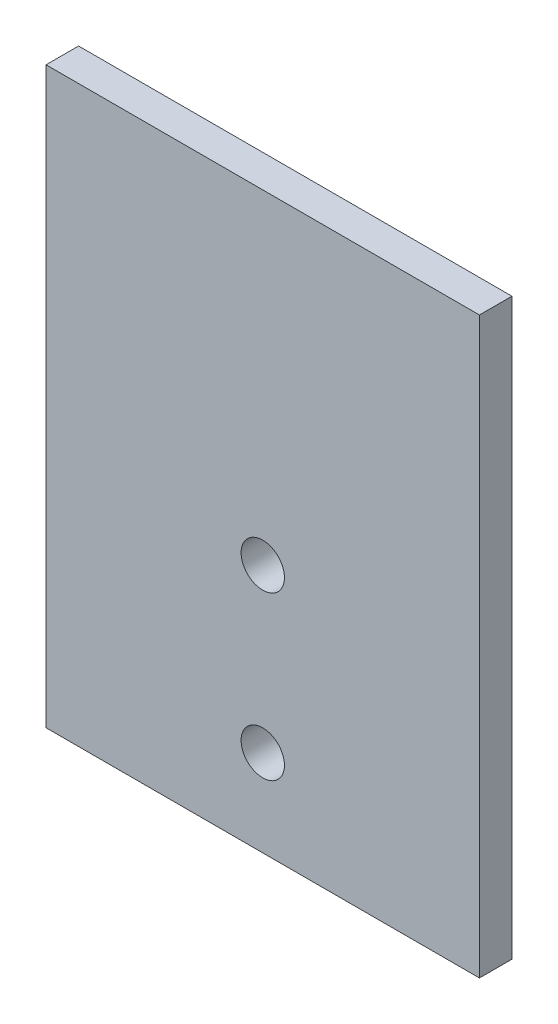
SolidWorks part; units mm, degrees
ref_plane "Piano frontale" through (0, 0, 0) normal (0, 0, 1) x (1, 0, 0)
ref_plane "Piano superiore" through (0, 0, 0) normal (0, 1, 0) x (1, 0, 0)
ref_plane "Piano destro" through (0, 0, 0) normal (1, 0, 0) x (0, 0, -1)
sketch "Schizzo1" plane through (0, 0, 0) normal (0, 0, 1) x (1, 0, 0)
  line L1 (-20, -26.5) -> (20, -26.5)
  line L2 (-20, -26.5) -> (-20, 26.5)
  line L3 (-20, 26.5) -> (20, 26.5)
  line L4 (20, -26.5) -> (20, 26.5)
  line L5 (-20, -26.5) -> (20, 26.5) construction
  line L6 (-20, 26.5) -> (20, -26.5) construction
  point P0 (0, 0)
  dimension "D1" = 40
  dimension "D2" = 53
extrude "Estrusione-Estrusione1" add sketch "Schizzo1" along normal blind 3
sketch "Schizzo2" plane through (0, 0, 3) normal (0, 0, 1) x (1, 0, 0)
  line L0 (-20, -26.5) -> (20, -26.5) construction
  line L1 (0, -55) -> (0, 55) construction
  circle A0 centre (0, -18.5) radius 2
  circle A1 centre (0, -3.5) radius 2
  dimension "D1" = 4
  dimension "D3" = 4
  dimension "D2" = 8
  dimension "D4" = 23
extrude "Taglio-Estrusione1" cut sketch "Schizzo2" against normal through all
